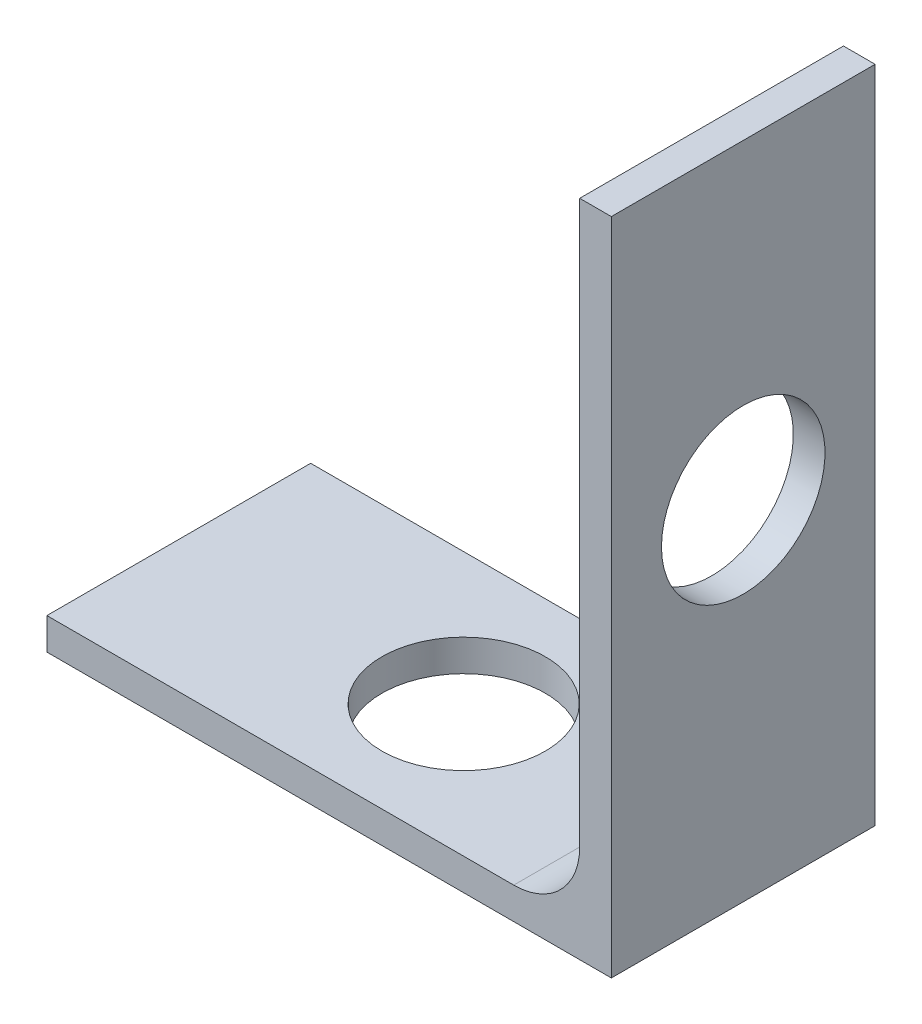
SolidWorks part; units mm, degrees
material "1060 Alloy"
ref_plane "Front Plane" through (0, 0, 0) normal (0, 0, 1) x (1, 0, 0)
ref_plane "Top Plane" through (0, 0, 0) normal (0, 1, 0) x (1, 0, 0)
ref_plane "Right Plane" through (0, 0, 0) normal (1, 0, 0) x (0, 0, -1)
sketch "Sketch1" plane through (0, 0, 0) normal (0, 0, 1) x (1, 0, 0)
  line L0 (0, 0) -> (27.178, 0)
  line L1 (27.178, 0) -> (27.178, 31.75)
  line L2 (0, 0) -> (0, 1.524)
  line L3 (0, 1.524) -> (25.654, 1.524)
  line L4 (25.654, 1.524) -> (25.654, 31.75)
  line L5 (25.654, 31.75) -> (27.178, 31.75)
  dimension "Height" = 31.75
  dimension "Depth" = 27.178
  dimension "Width2" = 1.524
  dimension "Width1" = 1.524
extrude "Boss-Extrude1" add sketch "Sketch1" along normal blind 12.7
sketch "Sketch2" plane through (25.654, 0, 0) normal (-1, 0, 0) x (0, 0, 1)
  line L8 (0, 31.75) -> (0, 1.524) construction
  line L9 (12.7, 0) -> (0, 0) construction
  circle A0 centre (6.35, 16.764) radius 3.937
  dimension "SideHoleDiameter" = 7.874
  dimension "SideHoleHorizontal" = 6.35
  dimension "SideHoleVertical" = 16.764
extrude "Cut-Extrude1" cut sketch "Sketch2" against normal blind 6.35
sketch "Sketch4" plane through (0, 1.524, 0) normal (0, 1, 0) x (1, 0, 0)
  line L0 (25.654, -12.7) -> (25.654, 0) construction
  line L6 (25.654, 0) -> (0, 0) construction
  circle A0 centre (13.716, -6.35) radius 3.937
  dimension "D1" = 7.874
  dimension "BottomHoleHorizontal" = 11.938
  dimension "BottomHoleVertical" = 6.35
extrude "Cut-Extrude2" cut sketch "Sketch4" against normal blind 6.35
fillet "Fillet2" radius 3.175 1 edges at (25.654, 1.524, 6.35)
equation "\"height\"=1.25"
equation "\"width\"= .06in"
equation "\"depth\"= 1.07in"
equation "\"extrusion\"= .5in"
equation "\"side hole diameter\"= .31in"
equation "\"horizontal side hole\"= .25in"
equation "\"vertical side hole\"= .66in"
equation "\"bottom hole diameter\"= .31in"
equation "\"horizontal bottom hole\"= .47in"
equation "\"vertical bottom hole\"= .25in"
